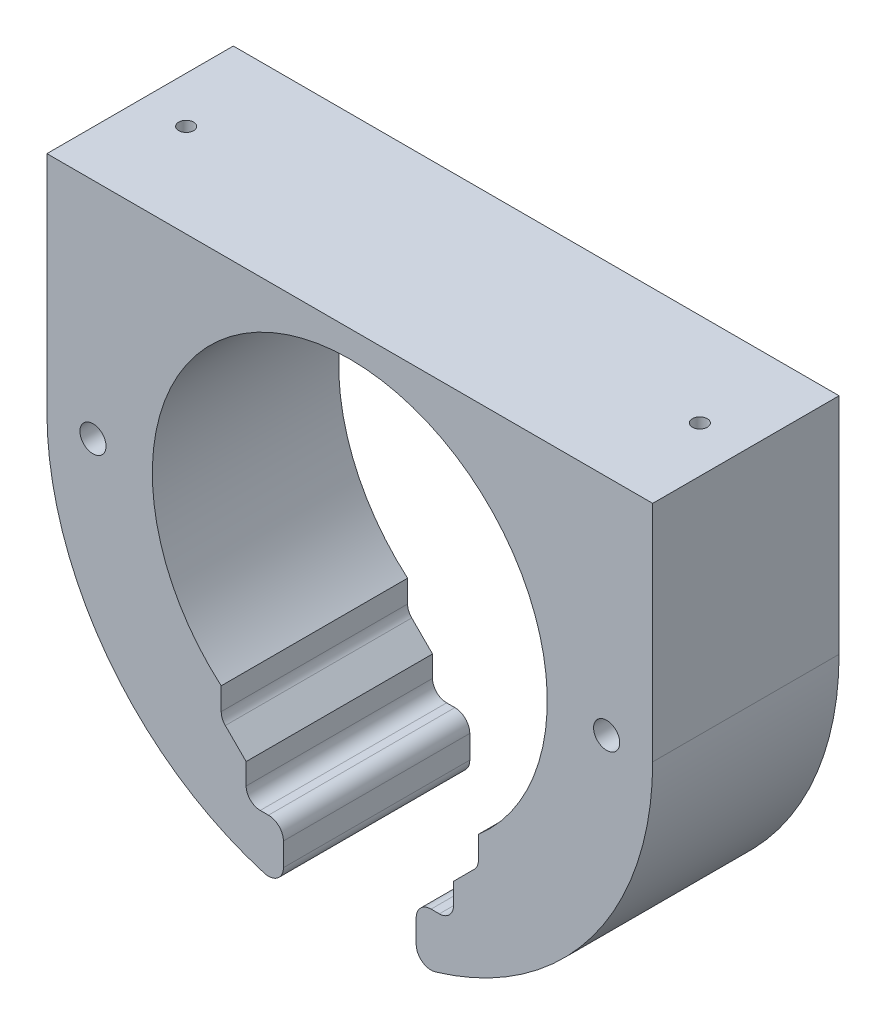
SolidWorks part; units mm, degrees
ref_plane "Front Plane" through (0, 0, 0) normal (0, 0, 1) x (1, 0, 0)
ref_plane "Top Plane" through (0, 0, 0) normal (0, 1, 0) x (1, 0, 0)
ref_plane "Right Plane" through (0, 0, 0) normal (1, 0, 0) x (0, 0, -1)
sketch "Sketch1" plane through (0, 0, 0) normal (0, 0, 1) x (1, 0, 0)
  line L0 (-20.6375, -7.6886) -> (-20.6375, 7.5673)
  line L2 (20.6375, 7.5673) -> (20.6375, -7.6886)
  line L4 (5.5399, -23.9227) -> (6.1028, -23.9227)
  line L7 (-20.6375, 7.5673) -> (20.6375, 7.5673)
  line L8 (4.5239, -26.5118) -> (4.5239, -24.9387)
  line L12 (-4.5239, -24.9387) -> (-4.5239, -26.5118)
  line L22 (8.7628, -19.4229) -> (8.7628, -17.8989)
  line L27 (-8.7628, -17.8989) -> (-8.7628, -19.4229)
  line L28 (-8.4813, -20.1025) -> (-7.0639, -21.52)
  line L29 (-7.0639, -21.52) -> (-7.0639, -22.9616)
  line L30 (-6.1028, -23.9227) -> (-5.5399, -23.9227)
  line L31 (7.0639, -22.9616) -> (7.0639, -21.52)
  line L32 (7.0639, -21.52) -> (8.4813, -20.1025)
  arc A0 (-13.0278, -4.3248) -> (-13.0278, -11.0523) centre (0, -7.6886) ccw
  arc A1 (13.0278, -11.0523) -> (13.0278, -4.3248) centre (0, -7.6886) ccw
  circle A2 centre (-17.5, -7.6886) radius 0.889
  circle A3 centre (17.5, -7.6886) radius 0.889
  arc A5 (5.5399, -23.9227) -> (4.5239, -24.9387) centre (5.5399, -24.9387) ccw
  arc A6 (-5.5399, -23.9227) -> (-4.5239, -24.9387) centre (-5.5399, -24.9387) cw
  arc A7 (5.8267, -27.4865) -> (20.6375, -7.6886) centre (0, -7.6886) ccw
  arc A8 (5.8267, -27.4865) -> (4.5239, -26.5118) centre (5.5399, -26.5118) cw
  arc A9 (-5.8267, -27.4865) -> (-4.5239, -26.5118) centre (-5.5399, -26.5118) ccw
  arc A11 (-20.6375, -7.6886) -> (-5.8267, -27.4865) centre (0, -7.6886) ccw
  arc A18 (8.4813, -20.1025) -> (8.7628, -19.4229) centre (7.8018, -19.4229) ccw
  arc A19 (8.7628, -17.8989) -> (13.0278, -11.0523) centre (0, -7.6886) ccw
  arc A21 (13.0278, -4.3248) -> (-13.0278, -4.3248) centre (0, -7.6886) ccw
  arc A23 (-13.0278, -11.0523) -> (-8.7628, -17.8989) centre (0, -7.6886) ccw
  arc A24 (-8.7628, -19.4229) -> (-8.4813, -20.1025) centre (-7.8018, -19.4229) ccw
  arc A25 (-7.0639, -22.9616) -> (-6.1028, -23.9227) centre (-6.1028, -22.9616) ccw
  arc A26 (6.1028, -23.9227) -> (7.0639, -22.9616) centre (6.1028, -22.9616) ccw
  point P37 (4.5239, -23.9227)
  dimension "D2" = 1.778
  dimension "D3" = 1.778
  dimension "D6" = 1.016
  dimension "D7" = 15.2559
  dimension "D8" = 1.016
  dimension "D9" = 17.5
  dimension "D10" = 17.5
  dimension "D4" = 2.54
  dimension "D5" = 2.54
extrude "Boss-Extrude1" add sketch "Sketch1" along normal blind 12.7
sketch "Sketch2" plane through (0, 7.5673, 0) normal (0, 1, 0) x (1, 0, 0)
  line L0 (20.6375, 0) -> (-20.6375, 0) construction
  circle A0 centre (-17.5, -6.35) radius 0.508
  circle A1 centre (17.5, -6.35) radius 0.508
  point P4 (0, 0)
  point P7 (0, 0)
  dimension "D1" = 1.016
  dimension "D2" = 1.016
  dimension "D3" = 17.5
  dimension "D4" = 17.5
extrude "Cut-Extrude1" cut sketch "Sketch2" against normal blind 12.7
